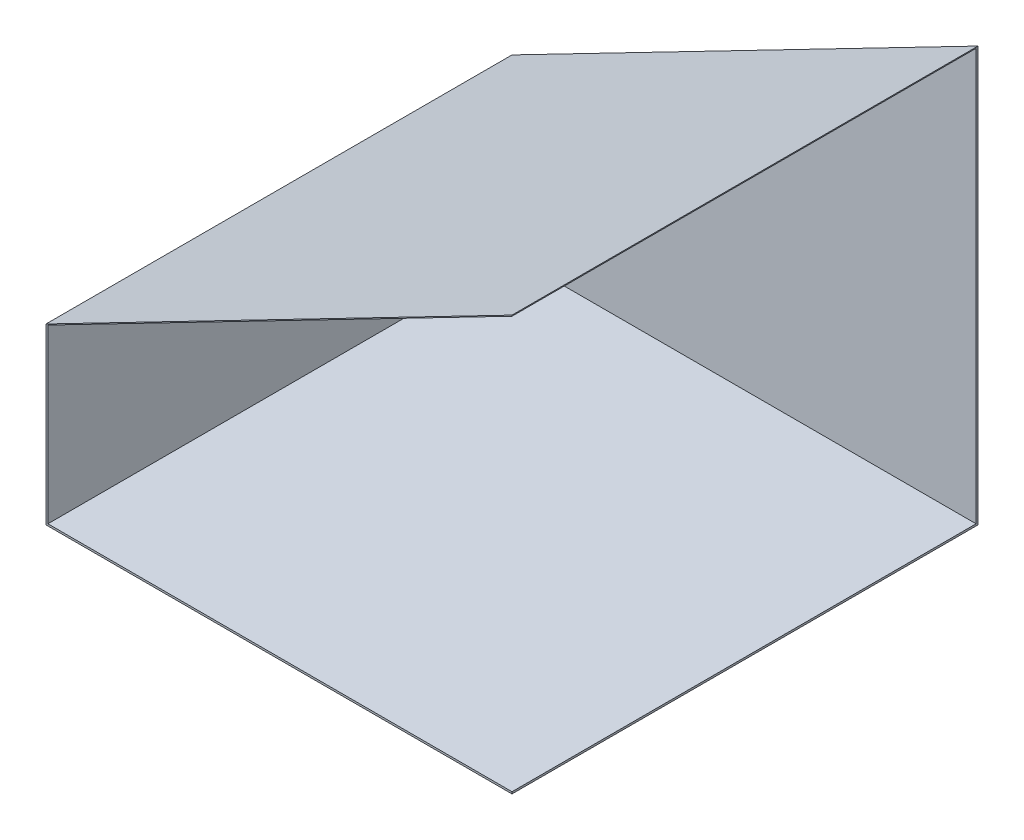
SolidWorks part; units mm, degrees
ref_plane "Front Plane" through (0, 0, 0) normal (0, 0, 1) x (1, 0, 0)
ref_plane "Top Plane" through (0, 0, 0) normal (0, 1, 0) x (1, 0, 0)
ref_plane "Right Plane" through (0, 0, 0) normal (1, 0, 0) x (0, 0, -1)
sketch "Sketch2" plane through (0, 0, 0) normal (0, 1, 0) x (1, 0, 0)
  line L1 (0, 0) -> (12192, 0)
  line L2 (0, 0) -> (0, 12192)
  line L3 (0, 12192) -> (12192, 12192)
  line L4 (12192, 0) -> (12192, 12192)
  dimension "D1" = 12192
  dimension "D2" = 12192
extrude "Boss-Extrude1" add sketch "Sketch2" along normal blind 50.8
sketch "Sketch3" plane through (0, 0, 0) normal (-1, 0, 0) x (0, 0, 1)
  line L1 (-12192, 0) -> (0, 0)
  line L2 (-12192, 0) -> (-12192, 4572)
  line L3 (-12192, 4572) -> (0, 4572)
  line L4 (0, 0) -> (0, 4572)
  dimension "D1" = 4572
extrude "Boss-Extrude2" add sketch "Sketch3" along normal blind 50.8
sketch "Sketch4" plane through (0, 0, -12192) normal (0, 0, -1) x (-1, 0, 0)
  line L1 (-12192, 0) -> (50.8, 0)
  line L2 (-12192, 0) -> (-12192, 4572)
  line L3 (-12192, 4572) -> (50.8, 4572)
  line L4 (50.8, 0) -> (50.8, 4572)
extrude "Boss-Extrude3" add sketch "Sketch4" along normal blind 50.8
sketch "Sketch5" plane through (0, 0, 0) normal (0, 0, 1) x (1, 0, 0)
  line L0 (12192, 4572) -> (12192, 50.8) construction
  line L1 (-50.8, 4572) -> (0, 4572)
  line L4 (12192, 10868.8294) -> (12192, 10895.0662)
  line L5 (-50.8, 4572) -> (12192, 10895.0662)
  line L6 (0, 4572) -> (12192, 10868.8294)
extrude "Boss-Extrude4" add sketch "Sketch5" against normal up to surface (12242.8 mm away) up to face at (6070.6, 2286, -12242.8)
sketch "Sketch6" plane through (0, 0, -12242.8) normal (0, 0, -1) x (-1, 0, 0)
  line L0 (-12192, 10895.0662) -> (-12192, 4572)
  line L1 (-12192, 4572) -> (50.8, 4572)
  line L2 (50.8, 4572) -> (-12192, 10895.0662)
extrude "Boss-Extrude5" add sketch "Sketch6" against normal blind 50.8
